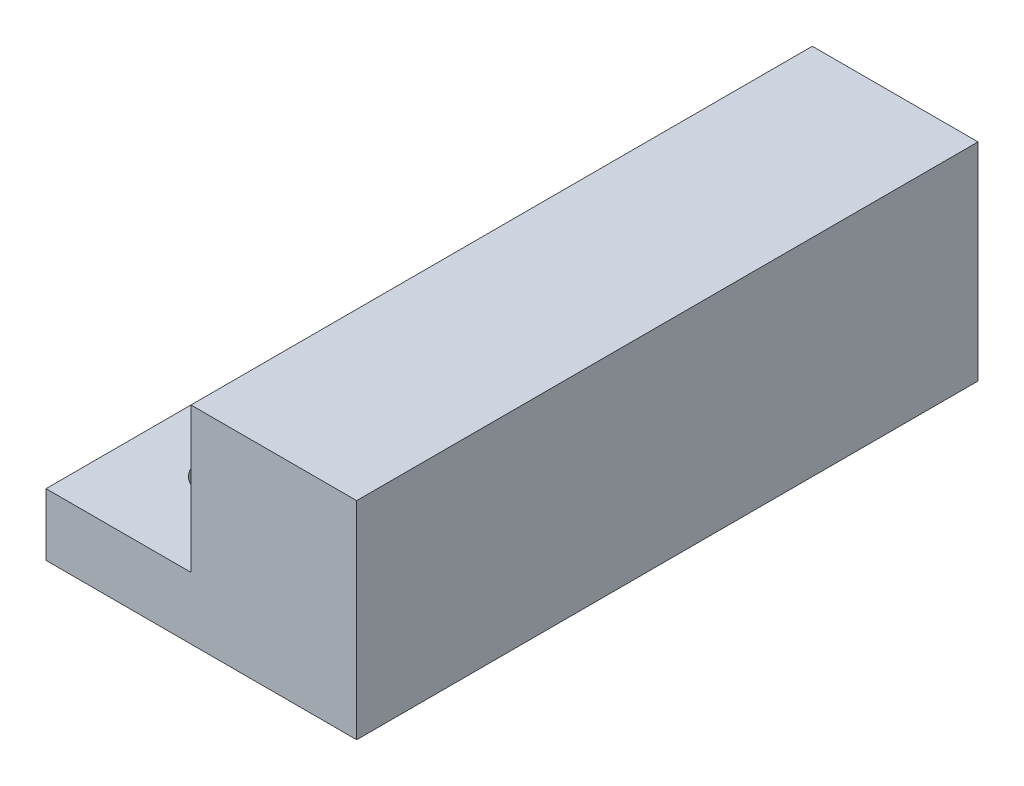
SolidWorks part; units mm, degrees
ref_plane "Front Plane" through (0, 0, 0) normal (0, 0, 1) x (1, 0, 0)
ref_plane "Top Plane" through (0, 0, 0) normal (0, 1, 0) x (1, 0, 0)
ref_plane "Right Plane" through (0, 0, 0) normal (1, 0, 0) x (0, 0, -1)
sketch "Sketch1" plane through (0, 0, 0) normal (0, 1, 0) x (1, 0, 0)
  line L0 (0, 0) -> (0, -25.4) construction
  line L1 (-13.97, 6.35) -> (5.08, 6.35)
  line L2 (-13.97, 6.35) -> (-13.97, -31.75)
  line L3 (-13.97, -31.75) -> (5.08, -31.75)
  line L4 (5.08, 6.35) -> (5.08, -31.75)
  circle A0 centre (0, 0) radius 1.905
  circle A1 centre (0, -25.4) radius 1.905
  point P6 (-13.97, -12.7)
  point P12 (0, -12.7)
  dimension "D1" = 25.4
  dimension "D2" = 3.81
  dimension "D3" = 3.81
  dimension "D4" = 5.08
  dimension "D5" = 38.1
  dimension "D6" = 19.05
extrude "Boss-Extrude1" add sketch "Sketch1" along normal blind 3.81
sketch "Sketch2" plane through (0, 3.81, 0) normal (0, 1, 0) x (1, 0, 0)
  line L0 (-13.97, 6.35) -> (-13.97, -31.75)
  line L1 (-13.97, -31.75) -> (-3.81, -31.75)
  line L2 (-13.97, -31.75) -> (5.08, -31.75) construction
  line L3 (-3.81, -31.75) -> (-3.81, 6.35)
  line L4 (5.08, 6.35) -> (-13.97, 6.35) construction
  line L5 (-3.81, 6.35) -> (-6.35, 6.35)
  line L6 (-6.35, 6.35) -> (-6.35, -29.21)
  line L7 (-6.35, -29.21) -> (-11.43, -29.21)
  line L8 (-11.43, -29.21) -> (-11.43, 6.35)
  line L9 (-11.43, 6.35) -> (-13.97, 6.35)
  dimension "D1" = 2.54
  dimension "D2" = 5.08
  dimension "D3" = 2.54
extrude "Boss-Extrude2" add sketch "Sketch2" along normal blind 6.35 contours L0 L1 L3 L5 L6 L7 L8 L9
sketch "Sketch3" plane through (0, 10.16, 0) normal (0, 1, 0) x (1, 0, 0)
  line L1 (-13.97, 6.35) -> (-3.81, 6.35)
  line L2 (-13.97, 6.35) -> (-13.97, -31.75)
  line L3 (-13.97, -31.75) -> (-3.81, -31.75)
  line L4 (-3.81, 6.35) -> (-3.81, -31.75)
extrude "Boss-Extrude3" add sketch "Sketch3" along normal blind 2.54
chamfer "Chamfer1" distance 1.27 angle 45 2 edges at (-6.35, 10.16, 11.43) (-11.43, 10.16, 11.43)
mirror "Mirror1" about plane through (5.08, 3.81, -6.35) normal (-1, 0, 0) of bodies 103
delete or keep bodies "Body-Delete/Keep 1" type delete bodies bodies 103
